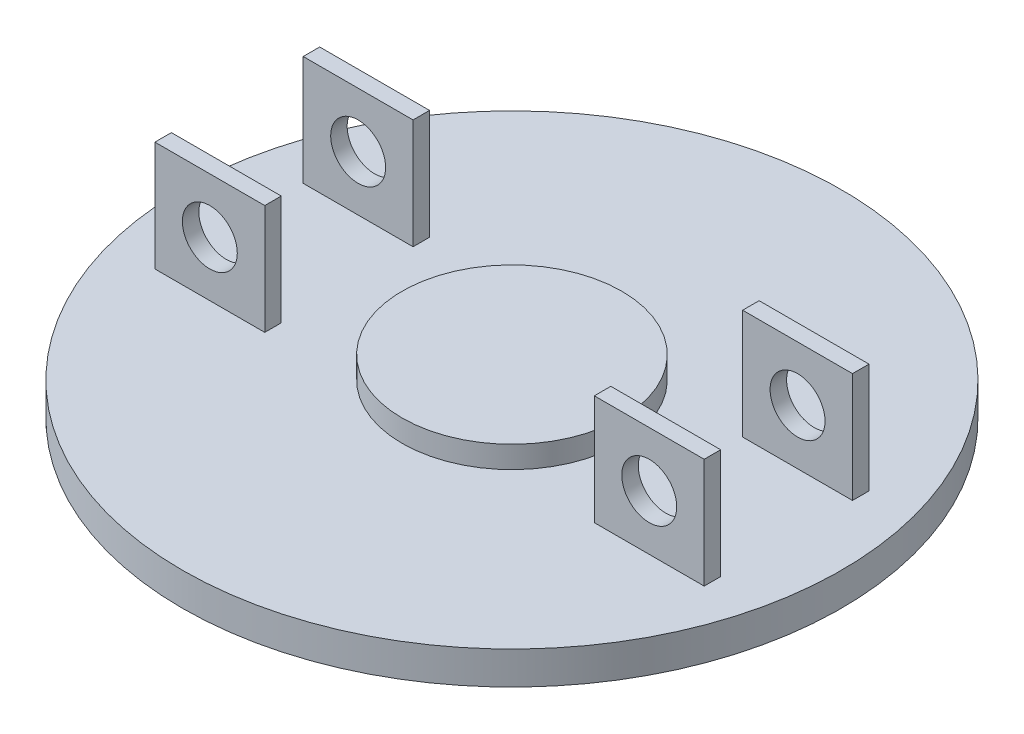
SolidWorks part; units mm, degrees
ref_plane "Front Plane" through (0, 0, 0) normal (0, 0, 1) x (1, 0, 0)
ref_plane "Top Plane" through (0, 0, 0) normal (0, 1, 0) x (1, 0, 0)
ref_plane "Right Plane" through (0, 0, 0) normal (1, 0, 0) x (0, 0, -1)
sketch "Sketch1" plane through (0, 0, 0) normal (0, 1, 0) x (1, 0, 0)
  circle A0 centre (0, 0) radius 30
  dimension "D1" = 60
extrude "Boss-Extrude1" add sketch "Sketch1" along normal blind 3
sketch "Sketch2" plane through (0, 3, 0) normal (0, 1, 0) x (1, 0, 0)
  circle A1 centre (0, 0) radius 10
extrude "Boss-Extrude2" add sketch "Sketch2" along normal blind 2
sketch "Sketch3" plane through (0, 3, 0) normal (0, 1, 0) x (1, 0, 0)
  line L0 (-30, 0) -> (-10, 0) construction
  line L1 (10, 0) -> (30, 0) construction
  line L3 (-25, 7.5) -> (-15, 7.5)
  line L4 (-25, 7.5) -> (-25, -7.5)
  line L5 (-25, -7.5) -> (-15, -7.5)
  line L6 (-15, 7.5) -> (-15, -7.5)
  line L7 (-25, 7.5) -> (-15, -7.5) construction
  line L8 (-25, -7.5) -> (-15, 7.5) construction
  line L9 (15, 7.5) -> (25, 7.5)
  line L10 (15, 7.5) -> (15, -7.5)
  line L11 (15, -7.5) -> (25, -7.5)
  line L12 (25, 7.5) -> (25, -7.5)
  line L13 (15, 7.5) -> (25, -7.5) construction
  line L14 (15, -7.5) -> (25, 7.5) construction
  circle A0 centre (0, 0) radius 30 construction
  point P5 (-20, 0)
  point P12 (20, 0)
  dimension "D1" = 10
  dimension "D2" = 15
  dimension "D3" = 10
  dimension "D4" = 15
extrude "Boss-Extrude3" add sketch "Sketch3" along normal blind 10
sketch "Sketch4" plane through (0, 0, 7.5) normal (0, 0, 1) x (1, 0, 0)
  line L1 (-25, 3) -> (-15, 3)
  line L2 (-25, 3) -> (-25, 13)
  line L3 (-25, 13) -> (-15, 13)
  line L4 (-15, 3) -> (-15, 13)
  line L5 (15, 3) -> (25, 3)
  line L6 (15, 3) -> (15, 13)
  line L7 (15, 13) -> (25, 13)
  line L8 (25, 3) -> (25, 13)
extrude "Cut-Extrude1" cut sketch "Sketch4" against normal blind 12 from offset 1.5 offset against normal yes
sketch "Sketch5" plane through (0, 0, 7.5) normal (0, 0, 1) x (1, 0, 0)
  line L0 (25, 13) -> (25, 3) construction
  line L1 (15, 13) -> (25, 13) construction
  line L2 (-25, 13) -> (-15, 13) construction
  line L3 (-15, 13) -> (-15, 3) construction
  circle A0 centre (20, 8) radius 2.5
  circle A1 centre (-20, 8) radius 2.5
  dimension "D1" = 5
  dimension "D4" = 5
  dimension "D5" = 5
  dimension "D2" = 5
  dimension "D3" = 5
extrude "Cut-Extrude2" cut sketch "Sketch5" against normal through all
